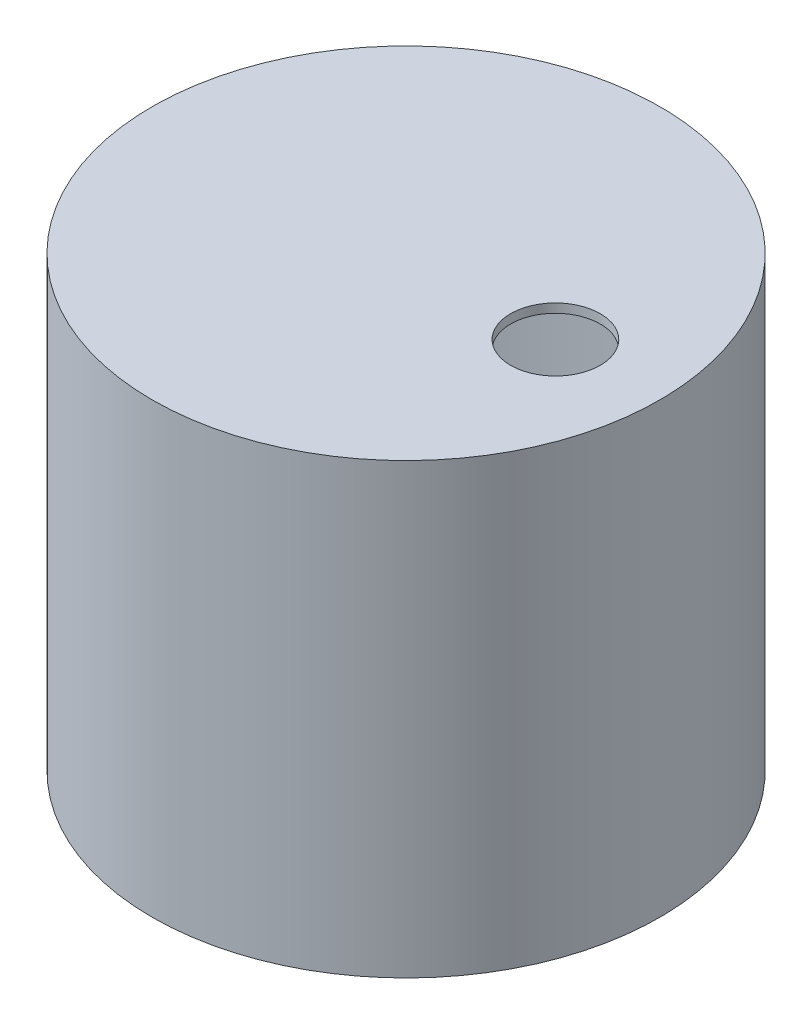
SolidWorks part; units mm, degrees
ref_plane "Front Plane" through (0, 0, 0) normal (0, 0, 1) x (1, 0, 0)
ref_plane "Top Plane" through (0, 0, 0) normal (0, 1, 0) x (1, 0, 0)
ref_plane "Right Plane" through (0, 0, 0) normal (1, 0, 0) x (0, 0, -1)
sketch "Reservoir Wall Sketch" plane through (0, 0, 0) normal (0, 1, 0) x (1, 0, 0)
  circle A0 centre (0, 0) radius 170
  circle A1 centre (0, 0) radius 166
  dimension "D1" = 340
  dimension "D2" = 332
extrude "Reservoir Wall + Skirt" add sketch "Reservoir Wall Sketch" along normal blind 300
sketch "Reservoir Floor Sketch" plane through (0, 0, 0) normal (0, 1, 0) x (1, 0, 0)
  circle A0 centre (0, 0) radius 170
  circle A1 centre (0, 0) radius 10
  dimension "D1" = 340
  dimension "D2" = 20
extrude "Reservoir Floor" add sketch "Reservoir Floor Sketch" along normal blind 6 from offset 40
sketch "Sealed Lid Sketch" plane through (0, 0, 0) normal (0, 1, 0) x (1, 0, 0)
  circle A0 centre (0, 0) radius 170
  circle A1 centre (100, 0) radius 30
  dimension "D1" = 340
  dimension "D3" = 60
  dimension "D2" = 100
extrude "Sealed Lid" add sketch "Sealed Lid Sketch" along normal blind 6 from offset 294
